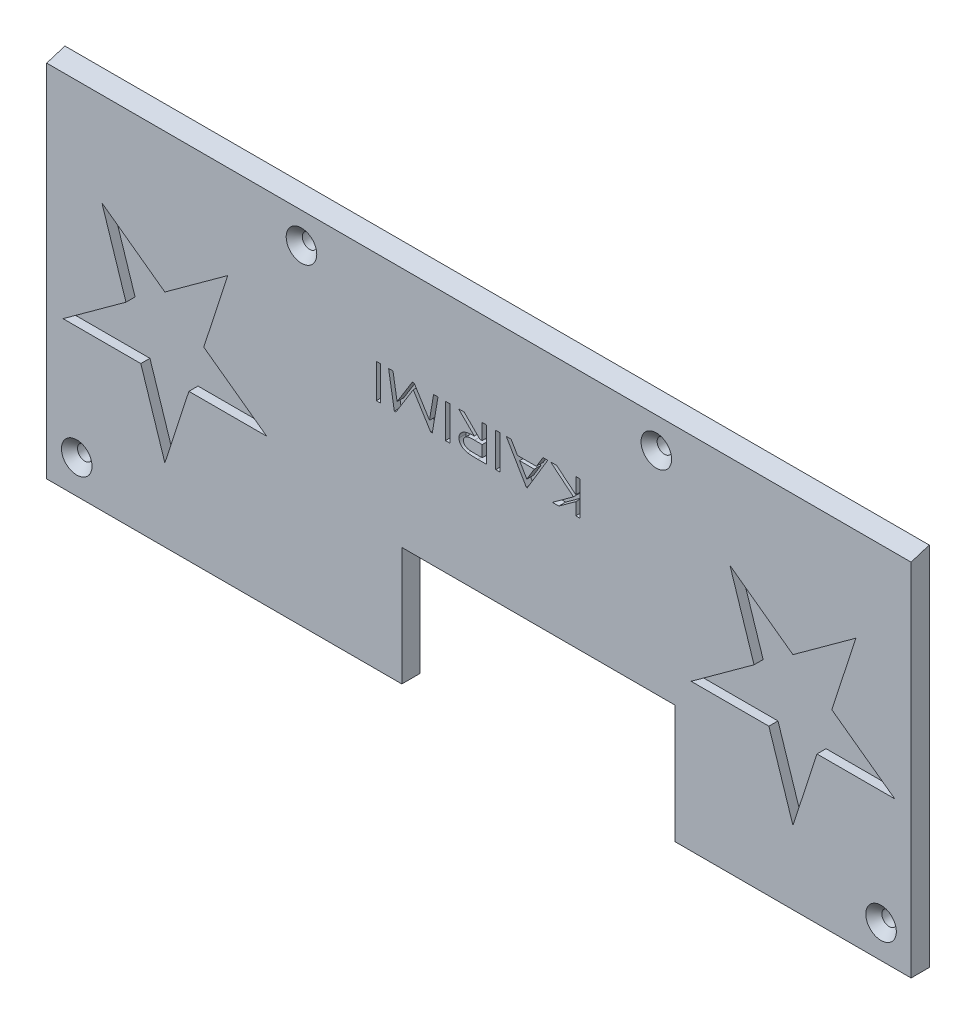
SolidWorks part; units mm, degrees
ref_plane "Alzado" through (0, 0, 0) normal (0, 0, 1) x (1, 0, 0)
ref_plane "Planta" through (0, 0, 0) normal (0, 1, 0) x (1, 0, 0)
ref_plane "Vista lateral" through (0, 0, 0) normal (1, 0, 0) x (0, 0, -1)
sketch "Croquis1" plane through (0, 0, 0) normal (0, 0, 1) x (1, 0, 0)
  line L0 (-32.321, -51.2841) -> (-32.321, 29.1352)
  line L1 (-32.321, 29.1352) -> (157.679, 29.1352)
  line L7 (157.679, 29.1352) -> (157.679, -51.2841)
  line L13 (75.7376, -48.4008) -> (100.7376, -48.4008) construction
  line L16 (-32.321, -51.2841) -> (45.7376, -51.2841)
  line L17 (45.7376, -25.2841) -> (105.7376, -25.2841)
  line L18 (157.679, -51.2841) -> (105.7376, -51.2841)
  line L19 (105.7376, -51.2841) -> (105.7376, -25.2841)
  line L20 (45.7376, -51.2841) -> (45.7376, -25.2841)
  circle A0 centre (23.679, 21.1352) radius 1.625
  circle A1 centre (101.679, 21.1352) radius 1.625
  circle A2 centre (-25.721, -43.8841) radius 1.625
  circle A3 centre (151.079, -44.0841) radius 1.625
  dimension "D1" = 3.25
  dimension "D2" = 23.679
  dimension "D3" = 45.7376
  dimension "D4" = 105.7376
  dimension "D5" = 101.679
  dimension "D6" = 151.079
  dimension "D7" = 157.679
  dimension "D8" = 25.721
  dimension "D9" = 32.321
  dimension "D10" = 21.1352
  dimension "D11" = 29.1352
  dimension "D12" = 25.2841
  dimension "D13" = 43.8841
  dimension "D14" = 44.0841
  dimension "D15" = 48.4008
  dimension "D16" = 51.2841
extrude "Saliente-Extruir1" add sketch "Croquis1" along normal blind 4
sketch "Croquis3" plane through (157.679, 0, 0) normal (1, 0, 0) x (0, 0, -1)
  line L0 (-4, 29.1352) -> (0, 29.1352)
  line L1 (-4, 29.1352) -> (0, 29.1352) construction
  line L2 (0, 29.1352) -> (-4, 27.88)
  line L3 (-4, -51.2841) -> (-4, 29.1352) construction
  line L4 (-4, 27.88) -> (-4, 29.1352)
  dimension "D1" = 1.2552
  dimension "D2" = 29.1352
extrude "Cortar-Extruir1" cut sketch "Croquis3" against normal up to vertex
sketch "Croquis4" plane through (0, 0, 4) normal (0, 0, 1) x (1, 0, 0)
  line L0 (157.679, -51.2841) -> (157.679, 27.88) construction
  line L1 (-32.321, 27.88) -> (157.679, 27.88) construction
  line L2 (-32.321, 27.88) -> (-32.321, -51.2841) construction
  circle A0 centre (23.679, 21.1352) radius 3.36
  circle A1 centre (101.679, 21.1352) radius 3.36
  circle A2 centre (-25.721, -43.8841) radius 3.36
  circle A3 centre (151.079, -44.0841) radius 3.36
  dimension "D1" = 6.7199
  dimension "D2" = 56
  dimension "D3" = 134
  dimension "D4" = 6.7448
  dimension "D5" = 6.6
  dimension "D6" = 183.4
  dimension "D7" = 71.7641
  dimension "D8" = 71.9641
extrude "Cortar-Extruir2" cut sketch "Croquis4" against normal blind 1.8 draft 44
sketch "Croquis6" plane through (0, 0, 4) normal (0, 0, 1) x (1, 0, 0)
  line L0 (19.6204, 0) -> (19.6204, -11.7021) construction
  line L1 (19.6204, -11.7021) -> (-32.321, -11.7021) construction
  line L2 (-32.321, 27.88) -> (-32.321, -51.2841) construction
  line L3 (0, 0) -> (19.6204, 0) construction
  line L4 (157.679, -51.2841) -> (157.679, 27.88) construction
  line L6 (157.679, -11.7021) -> (105.7376, -11.7021) construction
  line L29 (-32.321, 27.88) -> (157.679, 27.88) construction
  line L37 (16.0325, -18.9747) -> (-1.0664, -18.9747)
  line L38 (-6.3503, -35.2367) -> (16.0325, -18.9747) construction
  line L39 (16.0325, -18.9747) -> (7.483, 7.3378) construction
  line L40 (7.483, 7.3378) -> (-20.1836, 7.3378) construction
  line L41 (-20.1836, 7.3378) -> (-28.733, -18.9747) construction
  line L42 (-28.733, -18.9747) -> (-6.3503, -35.2367) construction
  line L43 (131.7083, -35.2367) -> (154.091, -18.9747) construction
  line L44 (154.091, -18.9747) -> (145.5416, 7.3378) construction
  line L45 (145.5416, 7.3378) -> (117.875, 7.3378) construction
  line L46 (117.875, 7.3378) -> (109.3256, -18.9747) construction
  line L47 (109.3256, -18.9747) -> (131.7083, -35.2367) construction
  line L48 (-28.733, -18.9747) -> (-14.8997, -8.9242)
  line L49 (7.483, 7.3378) -> (2.1992, -8.9242)
  line L50 (-6.3503, -35.2367) -> (-11.6341, -18.9747)
  line L51 (-20.1836, 7.3378) -> (-6.3503, -2.7126)
  line L52 (-11.6341, -18.9747) -> (-28.733, -18.9747)
  line L53 (-14.8997, -8.9242) -> (-20.1836, 7.3378)
  line L54 (-6.3503, -2.7126) -> (7.483, 7.3378)
  line L55 (2.1992, -8.9242) -> (16.0325, -18.9747)
  line L56 (-1.0664, -18.9747) -> (-6.3503, -35.2367)
  line L57 (109.3256, -18.9747) -> (126.4244, -18.9747)
  line L58 (154.091, -18.9747) -> (140.2577, -8.9242)
  line L59 (117.875, 7.3378) -> (123.1588, -8.9242)
  line L60 (131.7083, -35.2367) -> (136.9921, -18.9747)
  line L61 (145.5416, 7.3378) -> (131.7083, -2.7126)
  line L62 (126.4244, -18.9747) -> (131.7083, -35.2367)
  line L63 (140.2577, -8.9242) -> (145.5416, 7.3378)
  line L64 (136.9921, -18.9747) -> (154.091, -18.9747)
  line L65 (123.1588, -8.9242) -> (109.3256, -18.9747)
  line L66 (131.7083, -2.7126) -> (117.875, 7.3378)
  circle A0 centre (-6.3503, -11.7021) radius 19.0399 construction
  circle A1 centre (131.7083, -11.7021) radius 19.0399 construction
  dimension "D2" = 38.0798
  dimension "D4" = 38.0798
  dimension "D1" = 138.0586
  dimension "D3" = 86.1172
  dimension "D5" = 26.3125
  dimension "D6" = 26.3125
extrude "Cortar-Extruir3" cut sketch "Croquis6" against normal blind 2
sketch "Croquis9" plane through (0, 0, 4) normal (0, 0, 1) x (1, 0, 0)
  line L1 (117.875, 7.3378) -> (7.483, 7.3378) construction
  line L2 (-1.0664, -18.9747) -> (16.0325, -18.9747) construction
  line L3 (-32.321, 27.88) -> (157.679, 27.88) construction
  line L4 (62.679, 27.88) -> (62.679, 7.3378) construction
  text T0 "KAIRIMI" font "Century Gothic" height 7.5
  dimension "D1" = 26.3125
  dimension "D2" = 28.733
  dimension "D3" = 18.9747
extrude "Cortar-Extruir5" cut sketch "Croquis9" against normal blind 1.5
